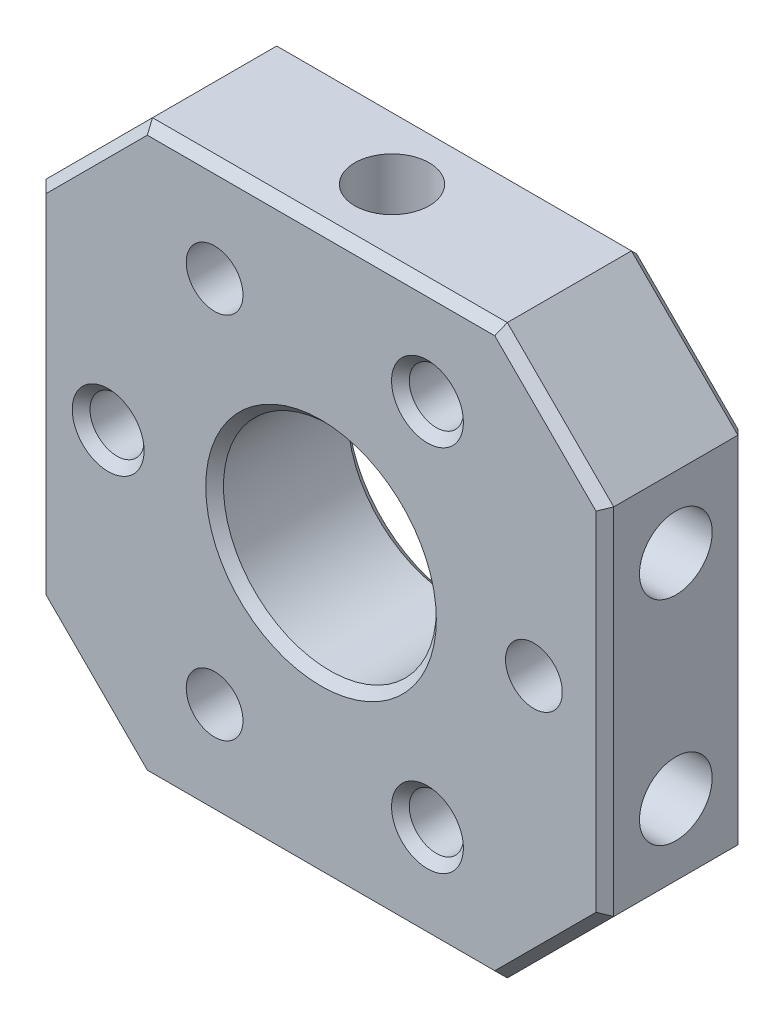
SolidWorks part; units mm, degrees
ref_plane "前视基准面" through (0, 0, 0) normal (0, 0, 1) x (1, 0, 0)
ref_plane "上视基准面" through (0, 0, 0) normal (0, 1, 0) x (1, 0, 0)
ref_plane "右视基准面" through (0, 0, 0) normal (1, 0, 0) x (0, 0, -1)
other "Configuration Table"
sketch "草图1" plane through (0, 0, 0) normal (0, 0, 1) x (1, 0, 0)
  line L1 (-16, 16) -> (16, 16)
  line L2 (-16, 16) -> (-16, -16)
  line L3 (-16, -16) -> (16, -16)
  line L4 (16, 16) -> (16, -16)
  line L5 (0, -16) -> (0, 16) construction
  line L6 (-16, 0) -> (16, 0) construction
  circle A0 centre (0, 0) radius 6
  circle A1 centre (0, 0) radius 18 construction
  circle A2 centre (0, 0) radius 12 construction
  dimension "D1" = 36
  dimension "D2" = 12
  dimension "D3" = 24
  dimension "D6" = 32
  dimension "D7" = 32
extrude "凸台-拉伸1" add sketch "草图1" along normal blind 8
sketch "草图2" plane through (0, 0, 8) normal (0, 0, 1) x (1, 0, 0)
  circle A0 centre (0, 0) radius 12 construction
  circle A1 centre (-12, 0) radius 1.525
  circle A2 centre (6, 10.3923) radius 1.525
  circle A3 centre (6, -10.3923) radius 1.525
  dimension "D1" = 24
  dimension "D2" = 3.05
  dimension "D3" = 3
extrude "切除-拉伸1" cut sketch "草图2" against normal blind 4
chamfer "倒角1" distance 6 angle 45 4 edges at (-16, -16, 4) (16, -16, 4) (-16, 16, 4) (16, 16, 4)
sketch "草图4" plane through (0, 16, 0) normal (0, 1, 0) x (1, 0, 0)
  line L1 (-10, -4) -> (10, -4) construction
  line L2 (-10, 0) -> (-10, -8) construction
  line L3 (10, -8) -> (10, 0) construction
  line L4 (10, 0) -> (-10, 0) construction
  circle A0 centre (0, -4) radius 2.1
  dimension "D1" = 4.2
  dimension "D2" = 10
  dimension "D3" = 4
extrude "切除-拉伸2" cut sketch "草图4" against normal blind 4.5
sketch "草图5" plane through (0, -16, 0) normal (0, -1, 0) x (1, 0, 0)
  line L0 (10, 0) -> (10, 8) construction
  line L1 (-10, 0) -> (10, 0) construction
  circle A0 centre (0, 4) radius 2.05
  dimension "D1" = 4.1
  dimension "D2" = 10
  dimension "D3" = 4
extrude "切除-拉伸3" cut sketch "草图5" against normal blind 4.5
sketch "草图6" plane through (16, 0, 0) normal (1, 0, 0) x (0, 0, -1)
  line L0 (-4, 10) -> (-4, -10) construction
  line L1 (0, 10) -> (-8, 10) construction
  line L2 (-8, -10) -> (0, -10) construction
  circle A0 centre (-4, 6) radius 2.05
  circle A1 centre (-4, -6) radius 2.05
  dimension "D1" = 4.1
  dimension "D2" = 4.1
  dimension "D3" = 4
  dimension "D4" = 4
extrude "切除-拉伸4" cut sketch "草图6" against normal blind 4.5
sketch "草图7" plane through (-16, 0, 0) normal (-1, 0, 0) x (0, 0, 1)
  line L0 (4, 10) -> (4, -10) construction
  line L1 (8, 10) -> (0, 10) construction
  line L2 (0, -10) -> (8, -10) construction
  circle A0 centre (4, 6) radius 2.05
  circle A1 centre (4, -6) radius 2.05
  dimension "D1" = 4.1
  dimension "D2" = 4.1
  dimension "D3" = 4
  dimension "D4" = 4
extrude "切除-拉伸5" cut sketch "草图7" against normal blind 4.5
chamfer "倒角2" distance 0.5 angle 45 21 edges at (-13, 13, 8) (0, 16, 8) (13, 13, 8) (16, 0, 8) (13, -13, 8) (0, -16, 8) (-13, -13, 8) (-16, 0, 8) (6, 0, 8) (7.525, -10.3923, 8) (7.525, 10.3923, 8) (-10.475, 0, 8) (6, 0, 0) (13, -13, 0) (16, 0, 0) (13, 13, 0) (0, 16, 0) (-13, 13, 0) (-16, 0, 0) (-13, -13, 0) (0, -16, 0)
sketch "草图8" plane through (0, 0, 0) normal (0, 0, -1) x (-1, 0, 0)
  line L0 (0, 0) -> (-15.5, 0) construction
  line L1 (-15.5, 9.7929) -> (-15.5, -9.7929) construction
  point P0 (-12, 0)
  point P1 (6, 10.3923)
  point P9 (6, -10.3923)
  dimension "D1" = 12
  dimension "D2" = 3
hole_wizard "M3 六角圆柱头螺钉的柱形沉头孔1" positions "草图8" profile "草图9" counterbore size "M3" standard "GB" end condition through all
sketch "草图9" plane through (12, 0, 0) normal (1, 0, 0) x (0, 1, 0)
  line L0 (0, 0) -> (0, 8)
  line L1 (0, 8) -> (1.6, 8)
  line L3 (1.6, 8) -> (1.6, 3.4)
  line L4 (1.6, 3.4) -> (3, 3.4)
  line L5 (3, 3.4) -> (3, 0)
  line L7 (3, 0) -> (0, 0)
  line L11 (0, -6.35) -> (0, 107.95) construction
  dimension "通孔孔直径" = 3.2
  dimension "通孔孔深度" = 8
  dimension "柱形沉头孔直径" = 6
  dimension "柱形沉头孔深度" = 3.4
